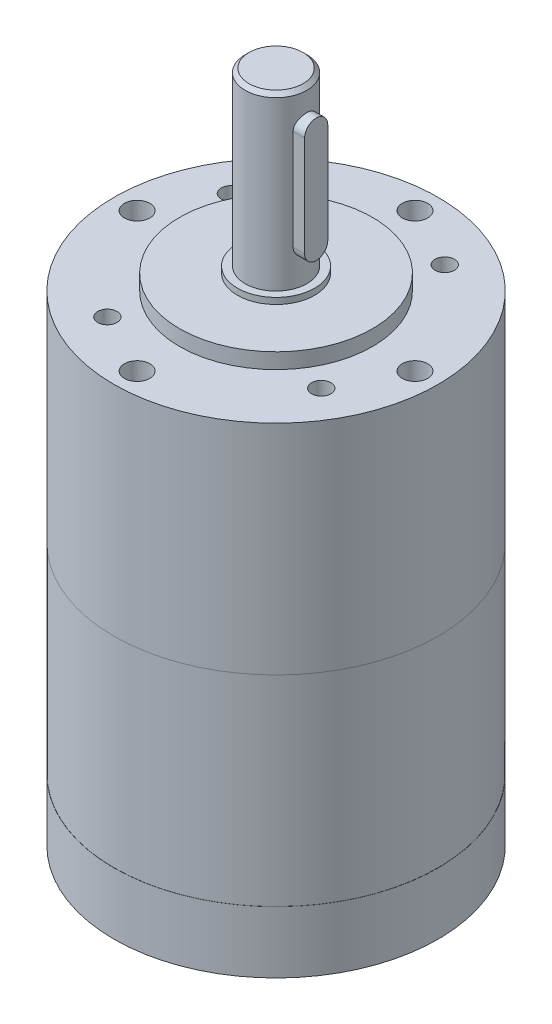
SolidWorks part; units mm, degrees
ref_plane "前视基准面" through (0, 0, 0) normal (0, 0, 1) x (1, 0, 0)
ref_plane "上视基准面" through (0, 0, 0) normal (0, 1, 0) x (1, 0, 0)
ref_plane "右视基准面" through (0, 0, 0) normal (1, 0, 0) x (0, 0, -1)
sketch "草图1" plane through (0, 0, 0) normal (0, 0, 1) x (1, 0, 0)
  line L0 (0, 99.8471) -> (0, -95.6721) construction
  line L1 (-90.3001, 0) -> (162.2719, 0) construction
  line L2 (0, 87.25) -> (4, 87.25)
  line L3 (4, 87.25) -> (4, 65.05)
  line L4 (4, 65.05) -> (5, 65.05)
  line L5 (5, 65.05) -> (5, 64.25)
  line L6 (5, 64.25) -> (12.5, 64.25)
  line L7 (12.5, 64.25) -> (12.5, 62.25)
  line L8 (12.5, 62.25) -> (21, 62.25)
  line L9 (21, 62.25) -> (21, 0)
  line L10 (21, 0) -> (0, 0)
  line L11 (0, 0) -> (0, 87.25)
  line L12 (21, 34) -> (20.98, 34)
  line L13 (20.98, 34) -> (20.98, 8)
  line L14 (20.98, 8) -> (21, 8)
  dimension "D1" = 8
  dimension "D2" = 42
  dimension "D3" = 25
  dimension "D4" = 2
  dimension "D5" = 2.8
  dimension "D6" = 25
  dimension "D7" = 10
  dimension "D8" = 62.25
  dimension "D9" = 8
  dimension "D10" = 26
  dimension "D11" = 0.02
revolve "旋转1" add sketch "草图1" angle 360 about L0
sketch "草图2" plane through (0, 0, 0) normal (1, 0, 0) x (0, 0, -1)
  line L0 (0, 0) -> (0, 103.5338) construction
  line L1 (0, 69.75) -> (0, 82.75) construction
  line L2 (-1.5, 69.75) -> (-1.5, 82.75)
  line L3 (1.5, 69.75) -> (1.5, 82.75)
  line L4 (4, 87.25) -> (-4, 87.25) construction
  line L5 (4, 87.25) -> (-4, 87.25) construction
  arc A0 (-1.5, 69.75) -> (1.5, 69.75) centre (0, 69.75) ccw
  arc A1 (1.5, 82.75) -> (-1.5, 82.75) centre (0, 82.75) ccw
  point P5 (0, 76.25)
  point P10 (0, 84.25)
  point P13 (0, 68.25)
  dimension "D1" = 3
  dimension "D2" = 3
  dimension "D3" = 16
extrude "切除-拉伸1" cut sketch "草图2" along normal through all from offset 2.2
chamfer "倒角1" distance 0.5 angle 45 1 edges at (0, 87.25, 4)
sketch "草图3" plane through (2.2, 0, 0) normal (1, 0, 0) x (0, 0, -1)
  line L2 (1.5, 69.75) -> (1.5, 82.75)
  line L3 (-1.5, 82.75) -> (-1.5, 69.75)
  line L4 (1.5, 69.75) -> (1.5, 82.75)
  line L5 (-1.5, 82.75) -> (-1.5, 69.75)
  arc A2 (-1.5, 69.75) -> (1.5, 69.75) centre (0, 69.75) ccw
  arc A3 (1.5, 82.75) -> (-1.5, 82.75) centre (0, 82.75) ccw
  arc A4 (-1.5, 69.75) -> (1.5, 69.75) centre (0, 69.75) ccw
  arc A5 (1.5, 82.75) -> (-1.5, 82.75) centre (0, 82.75) ccw
  dimension "D1" = 0
extrude "凸台-拉伸1" add sketch "草图3" along normal blind 3 separate body
sketch "草图4" plane through (0, 62.25, 0) normal (0, 1, 0) x (1, 0, 0)
  line L0 (29.9483, 0) -> (-30.9365, 0) construction
  line L1 (0, 35.9252) -> (0, -39.7183) construction
  line L2 (0, 0) -> (26.6589, -15.3915) construction
  point P5 (18, 0)
  point P8 (13.8564, -8)
  point P9 (0, -18)
  point P10 (-18, 0)
  point P11 (0, 18)
  point P12 (0, 0)
  point P16 (-8, -13.8564)
  point P17 (-13.8564, 8)
  point P18 (8, 13.8564)
  point P19 (0, 0)
  dimension "D1" = 4
  dimension "D2" = 36
  dimension "D3" = 30
  dimension "D4" = 16
  dimension "D5" = 4
hole_wizard "M3 螺纹孔1" positions "草图5" profile "草图6" tap size "M3" standard "GB"
sketch "草图5" plane through (0, 62.25, 0) normal (0, 1, 0) x (1, 0, 0)
  point P0 (13.8564, -8)
  point P3 (8, 13.8564)
  point P6 (-8, -13.8564)
  point P9 (-13.8564, 8)
sketch "草图6" plane through (13.8564, 62.25, 8) normal (1, 0, 0) x (0, 0, 1)
  line L0 (0, 0) -> (0, 10.7511)
  line L1 (0, 10.7511) -> (1.25, 10)
  line L2 (1.25, 10) -> (1.25, 0)
  line L5 (1.25, 0) -> (0, 0)
  line L10 (0, 10.7511) -> (-1.25, 10) construction
  line L11 (0, -6.35) -> (0, 107.95) construction
  dimension "螺纹孔钻头直径" = 2.5
  dimension "螺纹孔钻头深度" = 10
  dimension "导头角度" = 118
cosmetic thread "孔螺蚊线1" parameters "D1"=10, "D2"=3
cosmetic thread "孔螺蚊线2" parameters "D1"=10, "D2"=3
cosmetic thread "孔螺蚊线3" parameters "D1"=10, "D2"=3
cosmetic thread "孔螺蚊线4" parameters "D1"=10, "D2"=3
hole_wizard "M4 螺纹孔1" positions "草图7" profile "草图8" tap size "M4" standard "GB"
sketch "草图7" plane through (0, 62.25, 0) normal (0, 1, 0) x (1, 0, 0)
  point P0 (18, 0)
  point P3 (0, -18)
  point P6 (-18, 0)
  point P9 (0, 18)
sketch "草图8" plane through (18, 62.25, 0) normal (1, 0, 0) x (0, 0, 1)
  line L0 (0, 0) -> (0, 10.9914)
  line L1 (0, 10.9914) -> (1.65, 10)
  line L2 (1.65, 10) -> (1.65, 0)
  line L5 (1.65, 0) -> (0, 0)
  line L10 (0, 10.9914) -> (-1.65, 10) construction
  line L11 (0, -6.35) -> (0, 107.95) construction
  dimension "螺纹孔钻头直径" = 3.3
  dimension "螺纹孔钻头深度" = 10
  dimension "导头角度" = 118
cosmetic thread "孔螺蚊线5" parameters "D1"=10, "D2"=4
cosmetic thread "孔螺蚊线6" parameters "D1"=10, "D2"=4
cosmetic thread "孔螺蚊线7" parameters "D1"=10, "D2"=4
cosmetic thread "孔螺蚊线8" parameters "D1"=10, "D2"=4
